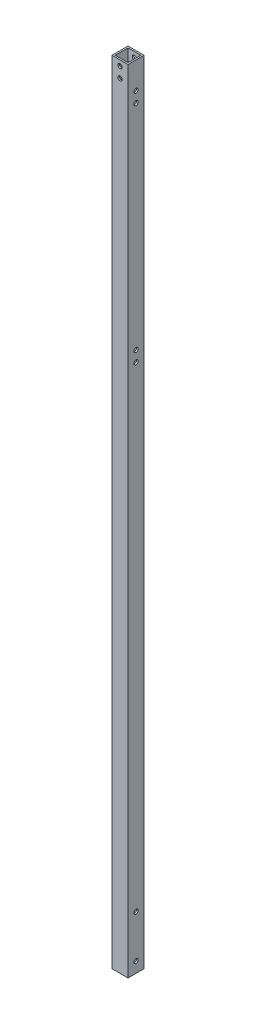
SolidWorks part; units mm, degrees
material "5052-H34"
ref_plane "正面" through (0, 0, 0) normal (0, 0, 1) x (1, 0, 0)
ref_plane "平面" through (0, 0, 0) normal (0, 1, 0) x (1, 0, 0)
ref_plane "右側面" through (0, 0, 0) normal (1, 0, 0) x (0, 0, -1)
sketch "ｽｹｯﾁ1" plane through (0, 0, 0) normal (0, 1, 0) x (1, 0, 0)
  line L1 (-7.5, 7.5) -> (7.5, 7.5)
  line L2 (-7.5, 7.5) -> (-7.5, -7.5)
  line L3 (-7.5, -7.5) -> (7.5, -7.5)
  line L4 (7.5, 7.5) -> (7.5, -7.5)
  line L5 (-7.5, 7.5) -> (7.5, -7.5) construction
  line L6 (-7.5, -7.5) -> (7.5, 7.5) construction
  point P0 (0, 0)
  dimension "D1" = 15
  dimension "D2" = 15
extrude "押し出し-薄板1" add sketch "ｽｹｯﾁ1" along normal blind 740 thin
sketch "ｽｹｯﾁ2" plane through (7.5, 0, 0) normal (1, 0, 0) x (0, 0, -1)
  line L0 (0, 0) -> (0, 50) construction
  line L1 (0, 740) -> (0, 715) construction
  line L2 (-7.5, 740) -> (7.5, 740) construction
  line L3 (0, 740) -> (0, 50740) construction
  circle A0 centre (0, 50) radius 2
  circle A1 centre (0, 10) radius 2
  circle A4 centre (0, 715) radius 2
  circle A5 centre (0, 705) radius 2
  circle A6 centre (0, 505) radius 2
  circle A7 centre (0, 495) radius 2
  dimension "D1" = 4
  dimension "D4" = 25
  dimension "D5" = 10
  dimension "D6" = 4
  dimension "D7" = 200
  dimension "D8" = 10
  dimension "D9" = 4
  dimension "D2" = 10
extrude "ｶｯﾄ - 押し出し1" cut sketch "ｽｹｯﾁ2" against normal through all
sketch "ｽｹｯﾁ3" plane through (0, 0, 7.5) normal (0, 0, 1) x (1, 0, 0)
  line L0 (0, 740) -> (0, 500) construction
  line L1 (-7.5, 740) -> (7.5, 740) construction
  circle A4 centre (0, 735) radius 2
  circle A5 centre (0, 725) radius 2
  dimension "D7" = 5
  dimension "D8" = 10
  dimension "D9" = 4
  dimension "D2" = 500
extrude "ｶｯﾄ - 押し出し2" cut sketch "ｽｹｯﾁ3" against normal through all
